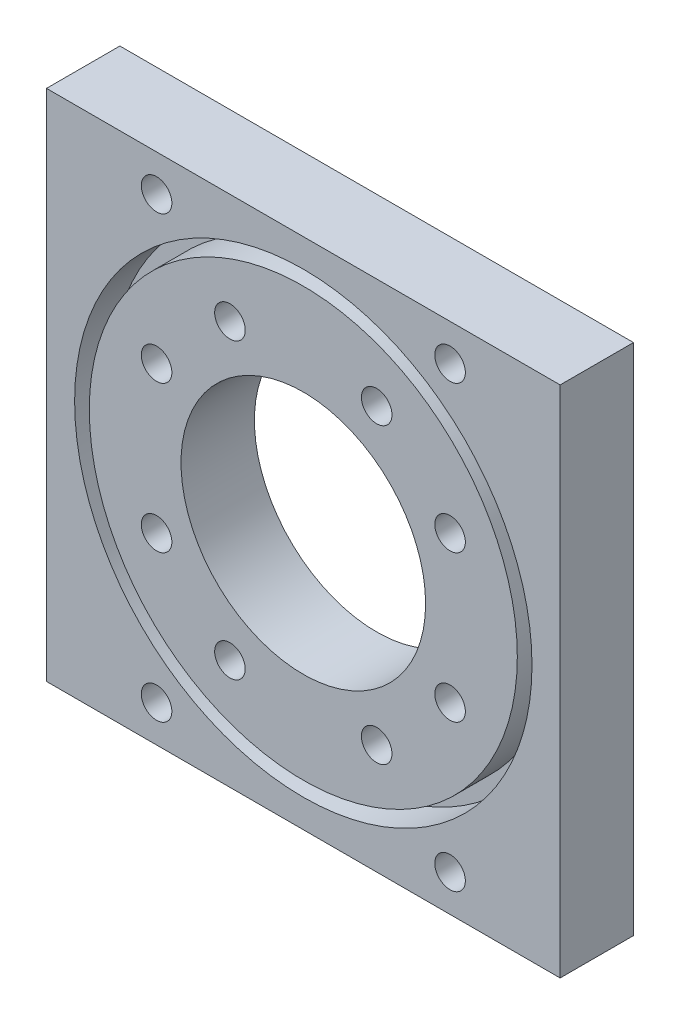
SolidWorks part; units mm, degrees
ref_plane "前基準面" through (0, 0, 0) normal (0, 0, 1) x (1, 0, 0)
ref_plane "上基準面" through (0, 0, 0) normal (0, 1, 0) x (1, 0, 0)
ref_plane "右基準面" through (0, 0, 0) normal (1, 0, 0) x (0, 0, -1)
sketch "草圖1" plane through (0, 0, 0) normal (0, 0, 1) x (1, 0, 0)
  line L0 (0, 0) -> (0, 6) construction
  line L1 (-21, -21) -> (21, -21)
  line L2 (-21, -21) -> (-21, 21)
  line L3 (-21, 21) -> (21, 21)
  line L4 (21, -21) -> (21, 21)
  line L5 (-21, -21) -> (21, 21) construction
  line L6 (-21, 21) -> (21, -21) construction
  line L7 (0, 6) -> (0, 12) construction
  line L8 (0, 12) -> (0, 18) construction
  line L9 (0, -12) -> (-6, -12)
  line L10 (0, 18) -> (-12, 18) construction
  line L11 (0, 18) -> (12, 18) construction
  line L12 (0, 12) -> (-6, 12) construction
  line L13 (0, 12) -> (6, 12) construction
  line L14 (0, 6) -> (-12, 6) construction
  line L15 (0, 6) -> (12, 6) construction
  line L16 (0, 0) -> (-17.9154, 0) construction
  line L17 (0, 0) -> (17.9154, 0) construction
  line L18 (0, 0) -> (0, -6) construction
  line L19 (0, -6) -> (0, -12) construction
  line L20 (0, -12) -> (0, -18) construction
  line L21 (0, -6) -> (-12, -6) construction
  line L22 (-6, -12) -> (0, -12)
  line L23 (0, -6) -> (12, -6) construction
  line L24 (0, -12) -> (6, -12)
  line L25 (0, -18) -> (-12, -18) construction
  line L26 (0, -18) -> (12, -18) construction
  circle A2 centre (-6, 12) radius 1.25
  circle A3 centre (-12, 6) radius 1.25
  circle A4 centre (-12, -6) radius 1.25
  circle A5 centre (-6, -12) radius 1.25
  circle A6 centre (6, 12) radius 1.25
  circle A7 centre (12, 6) radius 1.25
  circle A8 centre (12, -6) radius 1.25
  circle A9 centre (6, -12) radius 1.25
  circle A10 centre (-12, 18) radius 1.25
  circle A11 centre (12, 18) radius 1.25
  circle A12 centre (-12, -18) radius 1.25
  circle A13 centre (12, -18) radius 1.25
  circle A14 centre (0, 0) radius 10
  dimension "D9" = 2.5
  dimension "D10" = 20
  dimension "D1" = 42
  dimension "D2" = 42
  dimension "D4" = 6
  dimension "D6" = 12
  dimension "D7" = 6
  dimension "D8" = 12
extrude "填料-伸長1" add sketch "草圖1" along normal blind 6
sketch "草圖2" plane through (0, 0, 6) normal (0, 0, 1) x (1, 0, 0)
  circle A0 centre (0, 0) radius 17.5
  circle A2 centre (0, 0) radius 18.7
  dimension "D1" = 35
  dimension "D2" = 37.4
extrude "除料-伸長1" cut sketch "草圖2" against normal blind 3
